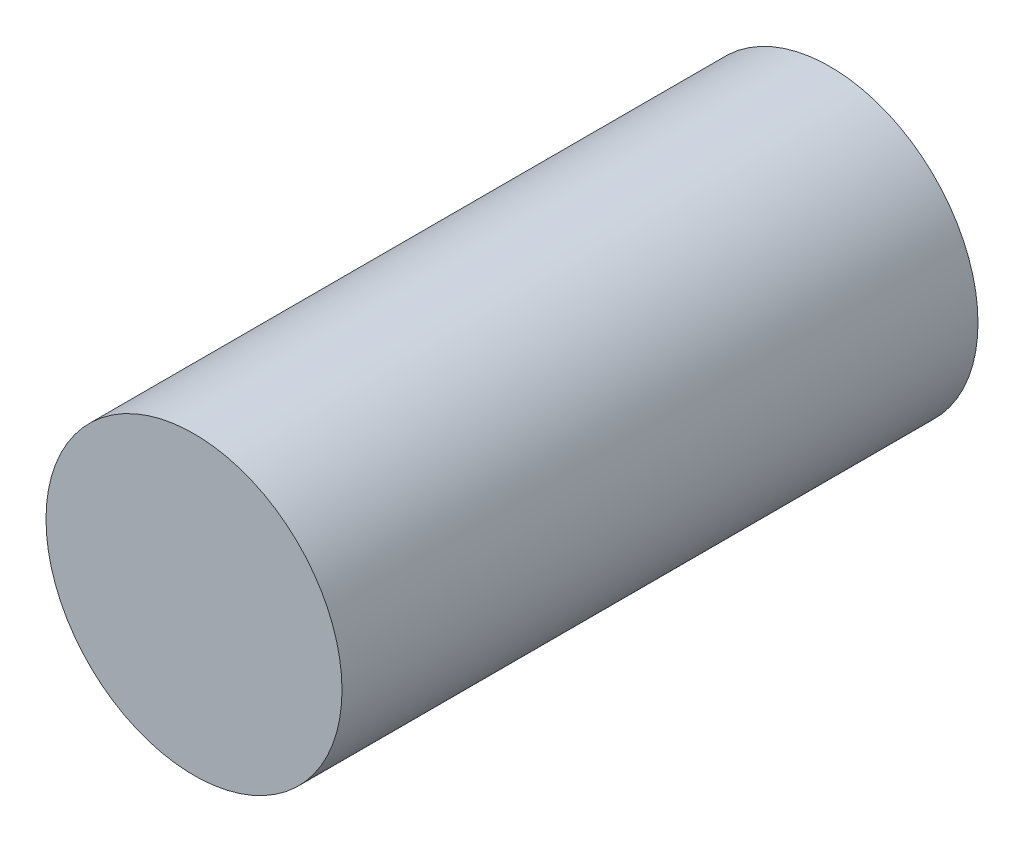
SolidWorks part; units mm, degrees
ref_plane "Front Plane" through (0, 0, 0) normal (0, 0, 1) x (1, 0, 0)
ref_plane "Top Plane" through (0, 0, 0) normal (0, 1, 0) x (1, 0, 0)
ref_plane "Right Plane" through (0, 0, 0) normal (1, 0, 0) x (0, 0, -1)
sketch "Sketch1" plane through (0, 0, 0) normal (0, 0, 1) x (1, 0, 0)
  circle A0 centre (0, 0) radius 3.7
  dimension "D1" = 7.4
extrude "Boss-Extrude1" add sketch "Sketch1" along normal blind 15.9
